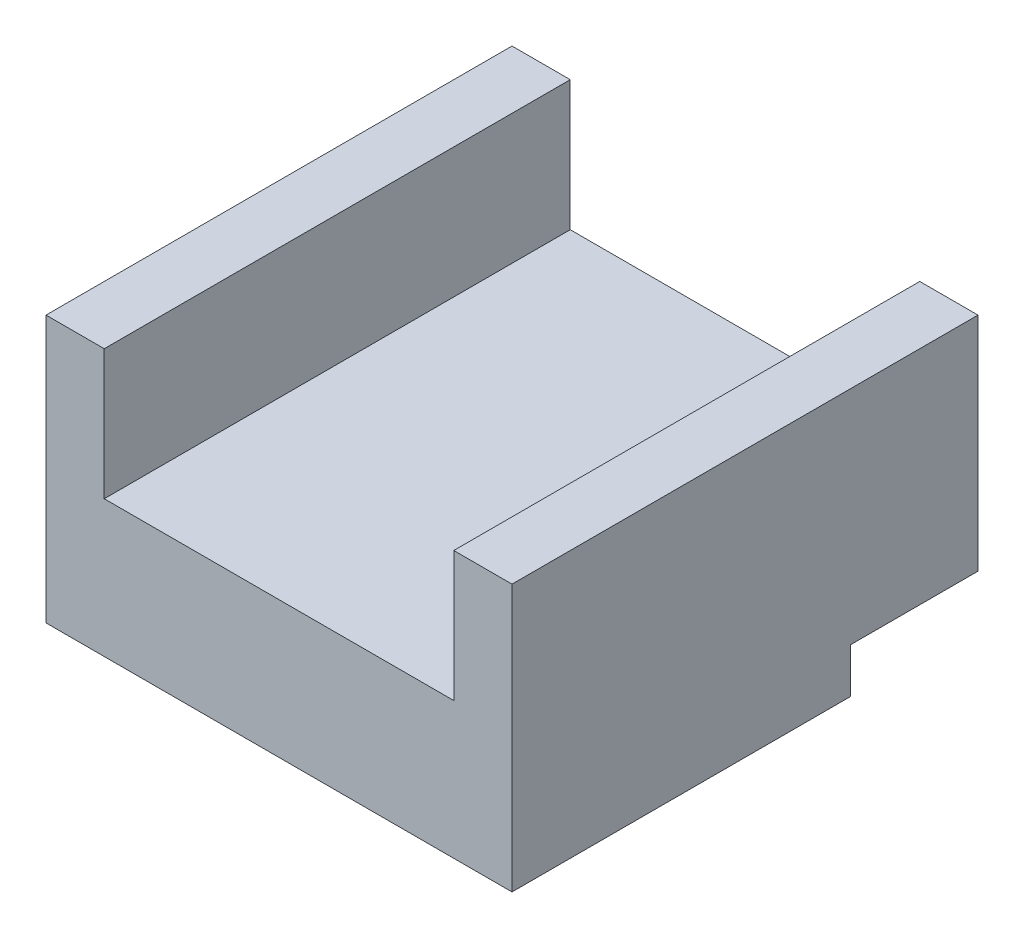
SolidWorks part; units mm, degrees
ref_plane "前视基准面" through (0, 0, 0) normal (0, 0, 1) x (1, 0, 0)
ref_plane "上视基准面" through (0, 0, 0) normal (0, 1, 0) x (1, 0, 0)
ref_plane "右视基准面" through (0, 0, 0) normal (1, 0, 0) x (0, 0, -1)
other "Configuration Table"
sketch "草图1" plane through (0, 0, 0) normal (0, 1, 0) x (1, 0, 0)
  line L1 (-10.4, -10.4) -> (10.4, -10.4)
  line L2 (-10.4, -10.4) -> (-10.4, 10.4)
  line L3 (-10.4, 10.4) -> (10.4, 10.4)
  line L4 (10.4, -10.4) -> (10.4, 10.4)
  line L5 (-10.4, -10.4) -> (10.4, 10.4) construction
  line L6 (-10.4, 10.4) -> (10.4, -10.4) construction
  point P0 (0, 0)
  dimension "D1" = 20.8
  dimension "D2" = 20.8
extrude "凸台-拉伸1" add sketch "草图1" along normal blind 6.1
sketch "草图2" plane through (0, 6.1, 0) normal (0, 1, 0) x (1, 0, 0)
  line L0 (-10.4, -10.4) -> (10.4, -10.4) construction
  line L1 (-10.4, 10.4) -> (-7.8, 10.4)
  line L2 (-10.4, 10.4) -> (-10.4, -10.4)
  line L3 (-10.4, -10.4) -> (-7.8, -10.4)
  line L4 (-7.8, 10.4) -> (-7.8, -10.4)
  line L6 (10.4, 10.4) -> (7.8, 10.4)
  line L7 (10.4, 10.4) -> (10.4, -10.4)
  line L8 (10.4, -10.4) -> (7.8, -10.4)
  line L9 (7.8, 10.4) -> (7.8, -10.4)
  dimension "D1" = 2.6
extrude "凸台-拉伸2" add sketch "草图2" along normal blind 11.9 from surface at -6.1 starting at face at (0, 0, 0)
sketch "草图3" plane through (0, 0, 0) normal (0, -1, 0) x (1, 0, 0)
  line L0 (-10.4, -10.4) -> (-10.4, 10.4) construction
  line L1 (-10.4, -10.4) -> (10.4, -10.4)
  line L2 (-10.4, -10.4) -> (-10.4, -4.7)
  line L3 (-10.4, -4.7) -> (10.4, -4.7)
  line L4 (10.4, -10.4) -> (10.4, -4.7)
  line L5 (10.4, 10.4) -> (10.4, -10.4) construction
  line L6 (10.4, -10.4) -> (-10.4, -10.4) construction
  dimension "D1" = 5.7
extrude "切除-拉伸1" cut sketch "草图3" against normal blind 2
